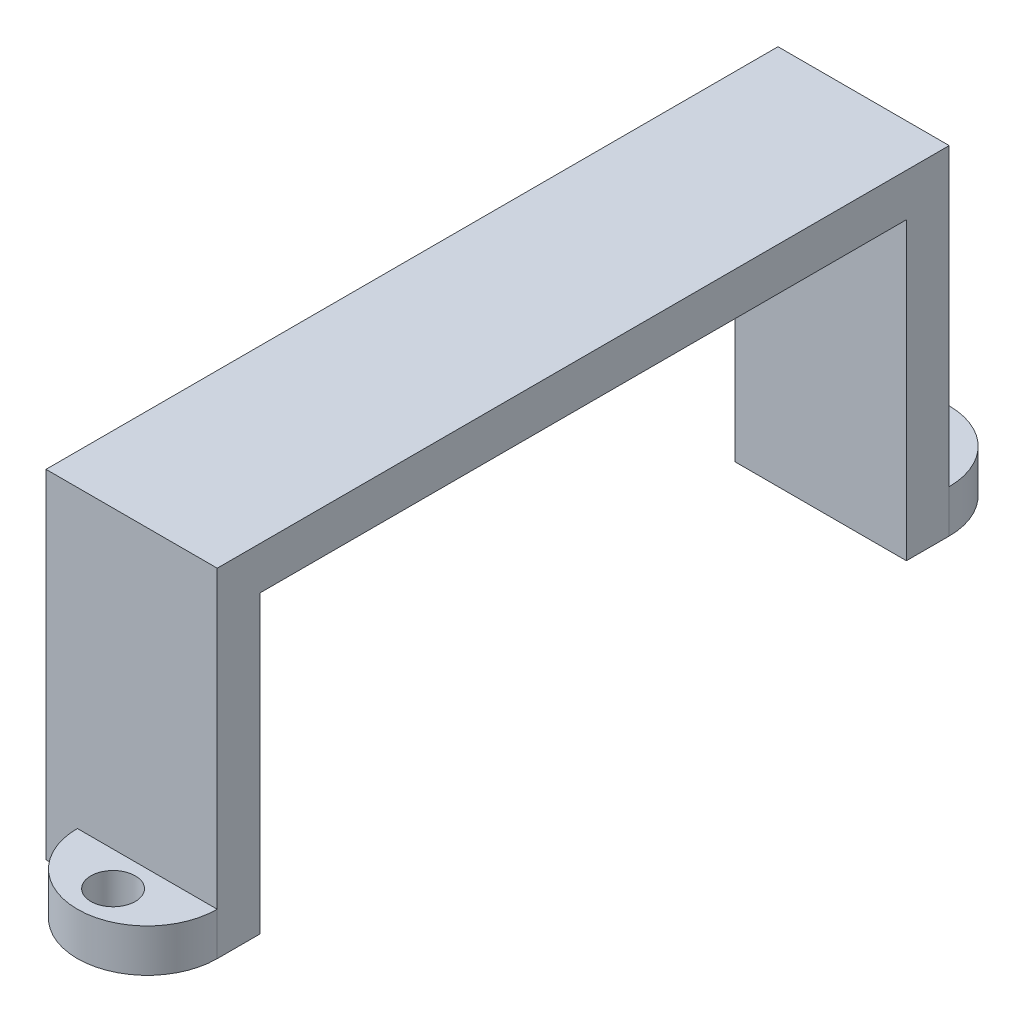
SolidWorks part; units mm, degrees
ref_plane "Front Plane" through (0, 0, 0) normal (0, 0, 1) x (1, 0, 0)
ref_plane "Top Plane" through (0, 0, 0) normal (0, 1, 0) x (1, 0, 0)
ref_plane "Right Plane" through (0, 0, 0) normal (1, 0, 0) x (0, 0, -1)
sketch "Sketch1" plane through (0, 0, 0) normal (0, 1, 0) x (1, 0, 0)
  line L1 (-24.2495, 15.8227) -> (-14.0895, 15.8227)
  line L2 (-24.2495, 15.8227) -> (-24.2495, 13.2827)
  line L3 (-24.2495, 13.2827) -> (-14.0895, 13.2827)
  line L4 (-14.0895, 15.8227) -> (-14.0895, 13.2827)
  line L5 (-24.2495, -25.0713) -> (-14.0895, -25.0713)
  line L6 (-24.2495, -25.0713) -> (-24.2495, -27.6113)
  line L7 (-24.2495, -27.6113) -> (-14.0895, -27.6113)
  line L8 (-14.0895, -25.0713) -> (-14.0895, -27.6113)
  dimension "D1" = 38.354
  dimension "D2" = 2.54
  dimension "D3" = 2.54
  dimension "D4" = 10.16
  dimension "D5" = 10.16
extrude "Boss-Extrude1" add sketch "Sketch1" along normal blind 17.526
sketch "Sketch2" plane through (0, 17.526, 0) normal (0, 1, 0) x (1, 0, 0)
  line L1 (-24.2495, 15.8227) -> (-14.0895, 15.8227)
  line L2 (-24.2495, 15.8227) -> (-24.2495, -27.6113)
  line L3 (-24.2495, -27.6113) -> (-14.0895, -27.6113)
  line L4 (-14.0895, 15.8227) -> (-14.0895, -27.6113)
extrude "Boss-Extrude2" add sketch "Sketch2" along normal blind 2.54
sketch "Sketch3" plane through (0, 0, 0) normal (0, -1, 0) x (1, 0, 0)
  line L0 (-22.3866, 27.6113) -> (-14.0895, 27.6113)
  line L1 (-22.3866, -15.8227) -> (-14.0895, -15.8227)
  line L2 (-14.0895, -13.2827) -> (-14.0895, -15.8227) construction
  line L3 (-14.0895, -15.8227) -> (-24.2495, -15.8227) construction
  line L4 (-14.0895, 27.6113) -> (-14.0895, 25.0713) construction
  line L5 (-24.2495, 27.6113) -> (-14.0895, 27.6113) construction
  arc A0 (-14.0895, 27.6113) -> (-22.3866, 27.6113) centre (-18.2381, 27.6113) ccw
  arc A1 (-14.0895, -15.8227) -> (-22.3866, -15.8227) centre (-18.2381, -15.8227) cw
  circle A2 centre (-18.2381, 29.6433) radius 1.3195
  circle A3 centre (-18.2381, -17.8547) radius 1.3499
  dimension "D1" = 47.498
  dimension "D2" = 2.032
extrude "Boss-Extrude3" add sketch "Sketch3" against normal blind 2.54
